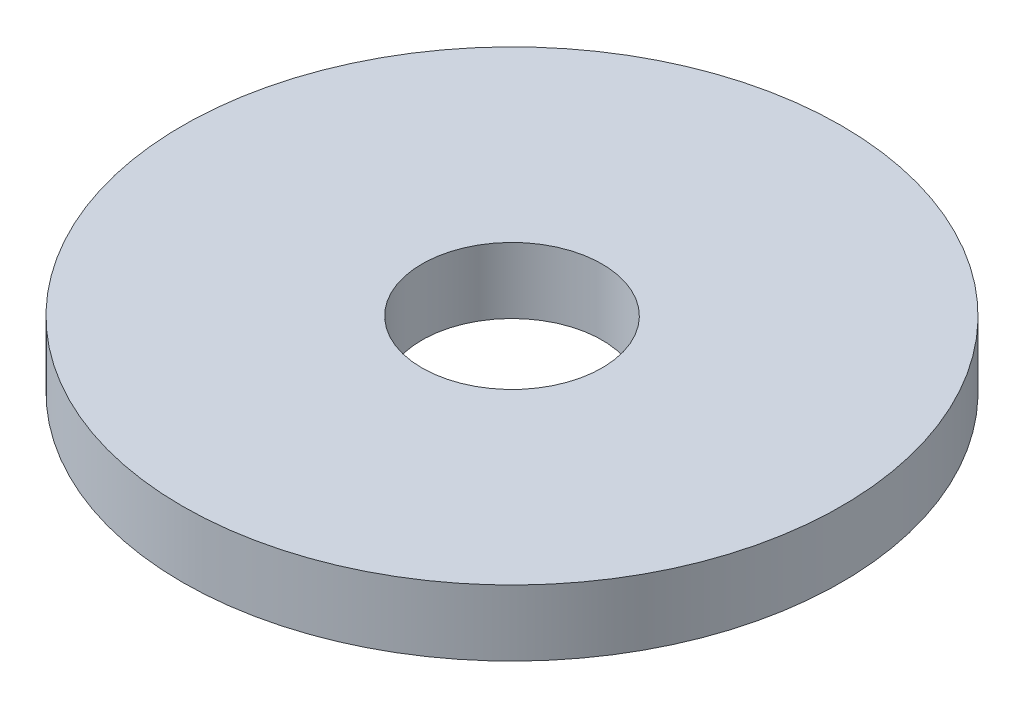
SolidWorks part; units mm, degrees
material "AISI 304"
ref_plane "前视基准面" through (0, 0, 0) normal (0, 0, 1) x (1, 0, 0)
ref_plane "上视基准面" through (0, 0, 0) normal (0, 1, 0) x (1, 0, 0)
ref_plane "右视基准面" through (0, 0, 0) normal (1, 0, 0) x (0, 0, -1)
sketch "草图1" plane through (0, 0, 0) normal (0, 1, 0) x (1, 0, 0)
  circle A0 centre (0, 0) radius 15
  circle A1 centre (0, 0) radius 4.1
  dimension "D1" = 8.2
  dimension "D2" = 30
extrude "凸台-拉伸1" add sketch "草图1" along normal blind 3
